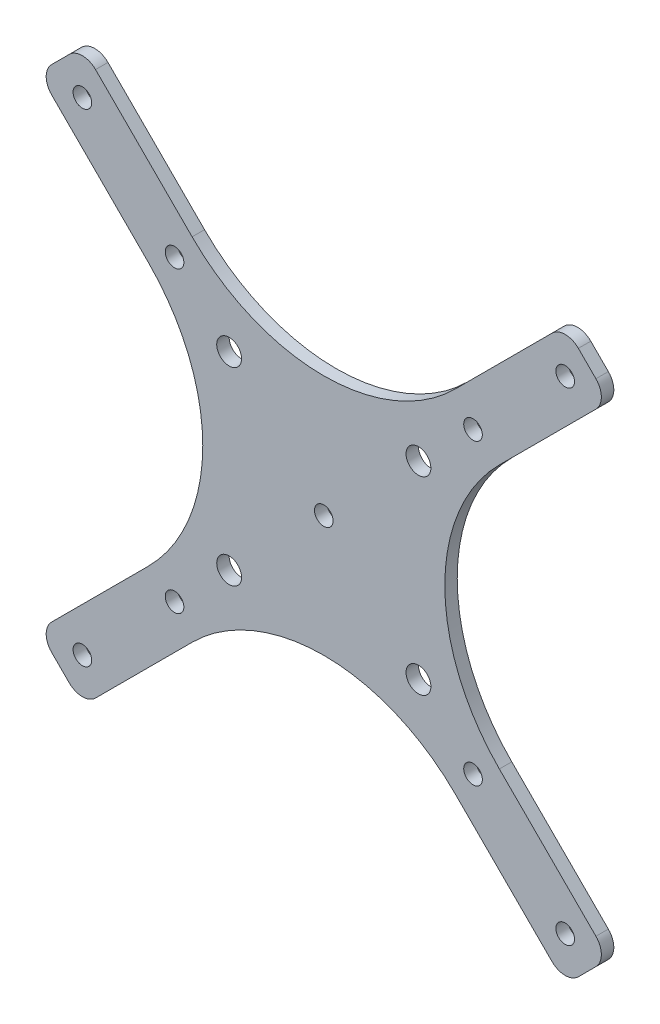
SolidWorks part; units mm, degrees
ref_plane "Alzado" through (0, 0, 0) normal (0, 0, 1) x (1, 0, 0)
ref_plane "Planta" through (0, 0, 0) normal (0, 1, 0) x (1, 0, 0)
ref_plane "Vista lateral" through (0, 0, 0) normal (1, 0, 0) x (0, 0, -1)
sketch "Croquis1" plane through (0, 0, 0) normal (0, 0, 1) x (1, 0, 0)
  line L0 (0, 0) -> (27.8544, 27.8544) construction
  line L1 (0, 0) -> (-42.4264, 42.4264) construction
  line L2 (-31.0962, 38.1673) -> (-21.2132, 28.2843)
  line L3 (15.25, -15.25) -> (-15.25, -15.25) construction
  line L4 (15.25, -15.25) -> (15.25, 15.25) construction
  line L5 (15.25, 15.25) -> (-15.25, 15.25) construction
  line L6 (-15.25, -15.25) -> (-15.25, 15.25) construction
  line L7 (15.25, -15.25) -> (-15.25, 15.25) construction
  line L8 (15.25, 15.25) -> (-15.25, -15.25) construction
  line L9 (21.2132, 28.2843) -> (31.0962, 38.1673)
  line L10 (-42.4264, 42.4264) -> (-38.8909, 45.9619)
  line L11 (-38.8909, 45.9619) -> (-31.0962, 38.1673)
  line L13 (-42.4264, 42.4264) -> (-45.9619, 38.8909)
  line L14 (-45.9619, 38.8909) -> (-38.1673, 31.0962)
  line L16 (38.8909, 45.9619) -> (31.0962, 38.1673)
  line L17 (42.4264, 42.4264) -> (38.8909, 45.9619)
  line L18 (42.4264, 42.4264) -> (45.9619, 38.8909)
  line L19 (-45.9619, -38.8909) -> (-38.1673, -31.0962)
  line L20 (0, 0) -> (-15.25, 0) construction
  line L21 (45.9619, 38.8909) -> (38.1673, 31.0962)
  line L22 (42.4264, -42.4264) -> (45.9619, -38.8909)
  line L23 (42.4264, -42.4264) -> (38.8909, -45.9619)
  line L24 (38.8909, -45.9619) -> (31.0962, -38.1673)
  line L27 (-38.8909, -45.9619) -> (-31.0962, -38.1673)
  line L28 (-42.4264, -42.4264) -> (-38.8909, -45.9619)
  line L29 (-42.4264, -42.4264) -> (-45.9619, -38.8909)
  line L30 (45.9619, -38.8909) -> (38.1673, -31.0962)
  line L31 (-31.0962, -38.1673) -> (-21.2132, -28.2843)
  line L32 (21.2132, -28.2843) -> (31.0962, -38.1673)
  line L33 (-38.1673, 31.0962) -> (-28.2843, 21.2132)
  line L34 (-28.2843, -21.2132) -> (-38.1673, -31.0962)
  line L35 (38.1673, 31.0962) -> (28.2843, 21.2132)
  line L36 (28.2843, -21.2132) -> (38.1673, -31.0962)
  circle A0 centre (-15.25, 15.25) radius 2
  circle A1 centre (-24.0416, 24.0416) radius 1.5
  circle A2 centre (-38.8909, 38.8909) radius 1.5
  circle A5 centre (38.8909, 38.8909) radius 1.5
  circle A6 centre (24.0416, 24.0416) radius 1.5
  circle A7 centre (15.25, 15.25) radius 2
  circle A8 centre (15.25, -15.25) radius 2
  circle A9 centre (24.0416, -24.0416) radius 1.5
  circle A10 centre (38.8909, -38.8909) radius 1.5
  circle A12 centre (-15.25, -15.25) radius 2
  circle A13 centre (-24.0416, -24.0416) radius 1.5
  circle A14 centre (-38.8909, -38.8909) radius 1.5
  circle A18 centre (0, 0) radius 1.5
  circle A20 centre (-16, -30) radius 3 construction
  circle A21 centre (-16, 30) radius 3 construction
  circle A24 centre (16, -30) radius 3 construction
  circle A25 centre (16, 30) radius 3 construction
  arc A91 (-21.2132, 28.2843) -> (21.2132, 28.2843) centre (0, 49.4975) ccw
  arc A92 (-21.2132, -28.2843) -> (21.2132, -28.2843) centre (0, -49.4975) cw
  arc A93 (-28.2843, 21.2132) -> (-28.2843, -21.2132) centre (-49.4975, 0) cw
  arc A94 (28.2843, 21.2132) -> (28.2843, -21.2132) centre (49.4975, 0) ccw
  point P35 (-34.9935, 42.0646)
  point P37 (44.1942, 40.6586)
  point P45 (44.1942, -40.6586)
  point P51 (-7.0711, 0)
  point P61 (-34.9935, -42.0646)
  dimension "D2" = 4
  dimension "D4" = 5
  dimension "D8" = 4
  dimension "D11" = 3
  dimension "D3" = 30
  dimension "D6" = 30
  dimension "D1" = 30.5
  dimension "D5" = 21
  dimension "D7" = 5
  dimension "D9" = 5
extrude "Saliente-Extruir1" add sketch "Croquis1" along normal blind 2
fillet "Redondeo3" radius 3 8 edges at (-45.9619, 38.8909, 1) (-38.8909, 45.9619, 1) (38.8909, 45.9619, 1) (45.9619, 38.8909, 1) (45.9619, -38.8909, 1) (38.8909, -45.9619, 1) (-45.9619, -38.8909, 1) (-38.8909, -45.9619, 1)
